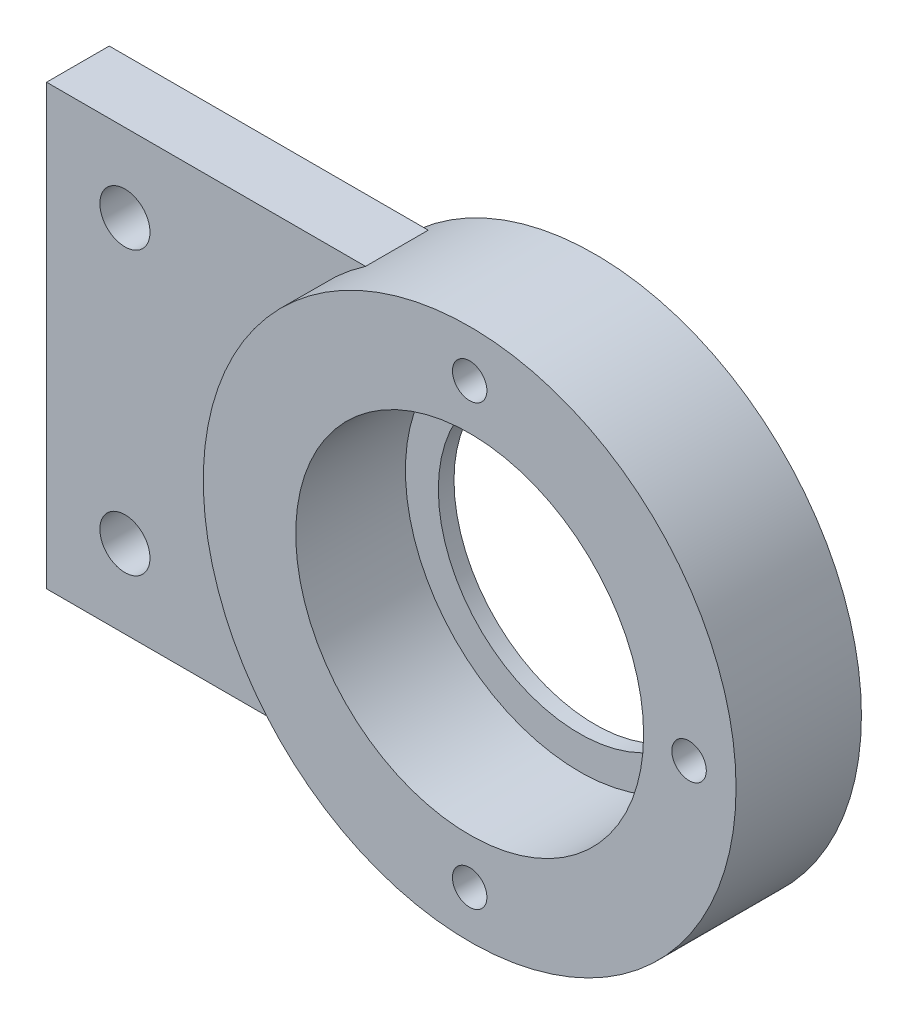
SolidWorks part; units mm, degrees
ref_plane "Front Plane" through (0, 0, 0) normal (0, 0, 1) x (1, 0, 0)
ref_plane "Top Plane" through (0, 0, 0) normal (0, 1, 0) x (1, 0, 0)
ref_plane "Right Plane" through (0, 0, 0) normal (1, 0, 0) x (0, 0, -1)
sketch "Bearing_housing_profile" plane through (0, 0, 0) normal (0, 0, 1) x (1, 0, 0)
  circle A0 centre (0, 0) radius 17
  circle A1 centre (0, 0) radius 11.1
  dimension "D1" = 34
  dimension "D2" = 22.2
extrude "Bearing_housing" add sketch "Bearing_housing_profile" along normal blind 7
sketch "Mounting_web_profile" plane through (0, 0, 0) normal (0, 0, 1) x (1, 0, 0)
  line L1 (-30, -14) -> (0, -14)
  line L2 (-30, -14) -> (-30, 14)
  line L3 (-30, 14) -> (0, 14)
  line L4 (0, -14) -> (0, 14)
  dimension "D1" = 30
  dimension "D2" = 28
  dimension "D3" = 14
extrude "Mounting_web" add sketch "Mounting_web_profile" along normal blind 4
sketch "Bearing_seat_profile" plane through (0, 0, 0) normal (0, 0, 1) x (1, 0, 0)
  circle A0 centre (0, 0) radius 11.1
  dimension "D1" = 22.2
extrude "Bearing_seat" cut sketch "Bearing_seat_profile" along normal through all from offset 50
sketch "Inner_outer_race_retaining_lip_profile" plane through (0, 0, 0) normal (0, 0, 1) x (1, 0, 0)
  circle A0 centre (0, 0) radius 17
  circle A1 centre (0, 0) radius 9
  dimension "D1" = 34
  dimension "D2" = 18
extrude "Inner_outer_race_retaining_lip" add sketch "Inner_outer_race_retaining_lip_profile" along normal blind 1 from offset 1
sketch "Standoff_fasteners_profile" plane through (0, 0, 0) normal (0, 0, 1) x (1, 0, 0)
  circle A0 centre (-25, -9) radius 1.6
  circle A1 centre (-25, 9) radius 1.6
  dimension "D1" = 3.2
  dimension "D2" = 3.2
  dimension "D3" = 25
  dimension "D4" = 9
  dimension "D5" = 9
extrude "Standoff_fasteners" cut sketch "Standoff_fasteners_profile" along normal through all from offset 50
sketch "Bearing_keeper_fasteners_profile" plane through (0, 0, 0) normal (0, 0, 1) x (1, 0, 0)
  circle A0 centre (14, 0) radius 1.1
  circle A1 centre (0, -14) radius 1.1
  circle A2 centre (0, 14) radius 1.1
  dimension "D1" = 2.2
  dimension "D2" = 2.2
  dimension "D3" = 2.2
  dimension "D4" = 14
  dimension "D5" = 14
  dimension "D6" = 14
extrude "Bearing_keeper_fasteners" cut sketch "Bearing_keeper_fasteners_profile" along normal through all from offset 50
